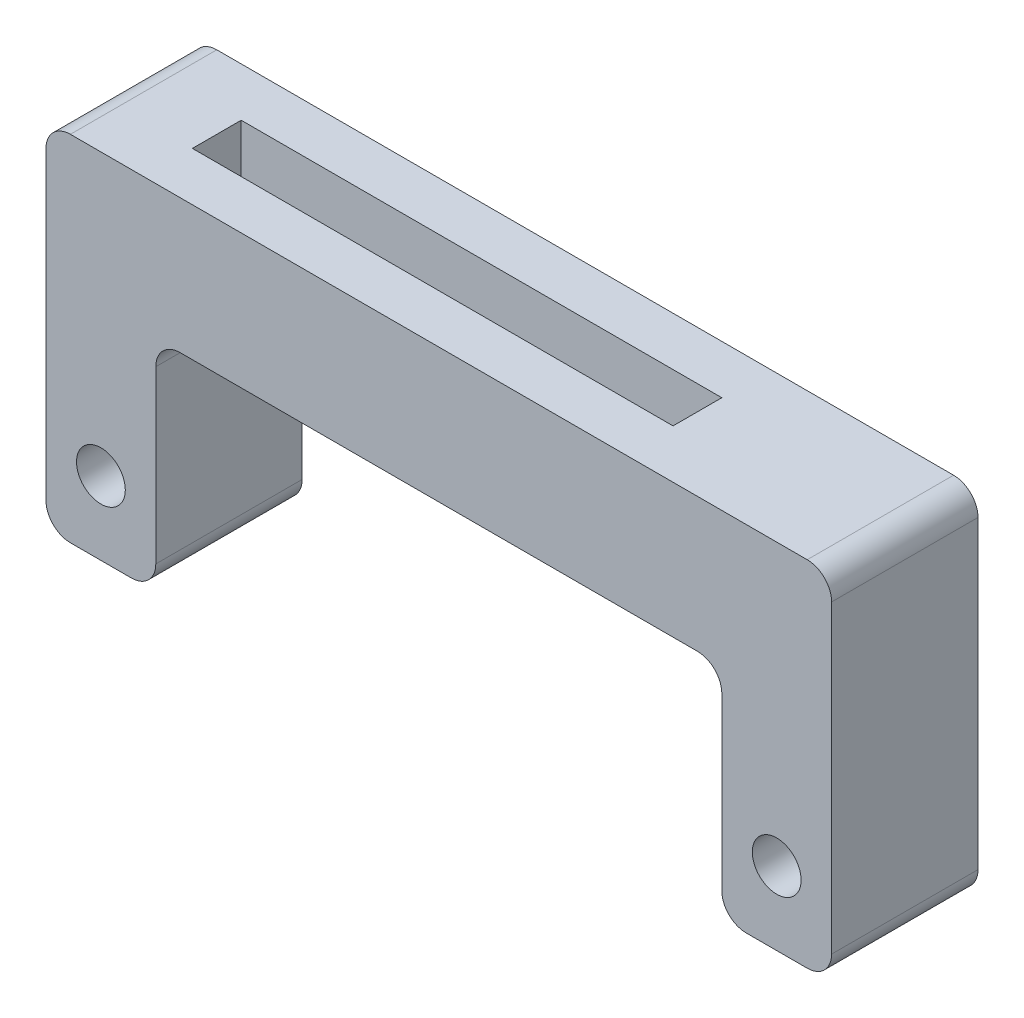
SolidWorks part; units mm, degrees
ref_plane "Front Plane" through (0, 0, 0) normal (0, 0, 1) x (1, 0, 0)
ref_plane "Top Plane" through (0, 0, 0) normal (0, 1, 0) x (1, 0, 0)
ref_plane "Right Plane" through (0, 0, 0) normal (1, 0, 0) x (0, 0, -1)
sketch "Sketch2" plane through (0, 0, 0) normal (0, 0, 1) x (1, 0, 0)
  line L1 (-16.1, -7.25) -> (16.1, -7.25)
  line L2 (-16.1, -7.25) -> (-16.1, 7.25)
  line L3 (-16.1, 7.25) -> (16.1, 7.25)
  line L4 (16.1, -7.25) -> (16.1, 7.25)
  line L5 (-16.1, -7.25) -> (16.1, 7.25) construction
  line L6 (-16.1, 7.25) -> (16.1, -7.25) construction
  point P0 (0, 0)
  dimension "D1" = 14.5
  dimension "D2" = 32.2
extrude "Boss-Extrude1" add sketch "Sketch2" along normal mid plane 6
sketch "Sketch3" plane through (0, 7.25, 0) normal (0, 1, 0) x (1, 0, 0)
  line L0 (-16.1, -3) -> (-16.1, 3) construction
  line L1 (-12.1, 1) -> (7.6, 1)
  line L2 (-12.1, 1) -> (-12.1, -1)
  line L3 (-12.1, -1) -> (7.6, -1)
  line L4 (7.6, 1) -> (7.6, -1)
  line L5 (16.1, -3) -> (16.1, 3) construction
  line L6 (16.1, 3) -> (-16.1, 3) construction
  dimension "D1" = 2
  dimension "D2" = 4
  dimension "D3" = 8.5
  dimension "D4" = 2
extrude "Cut-Extrude1" cut sketch "Sketch3" against normal blind 2.5
sketch "Sketch4" plane through (0, 0, 3) normal (0, 0, 1) x (1, 0, 0)
  line L0 (-16.1, -7.25) -> (16.1, -7.25) construction
  line L1 (-11.6, -7.25) -> (11.6, -7.25)
  line L2 (-11.6, -7.25) -> (-11.6, 1.75)
  line L3 (-11.6, 1.75) -> (11.6, 1.75)
  line L4 (11.6, -7.25) -> (11.6, 1.75)
  line L5 (-16.1, 7.25) -> (-16.1, -7.25) construction
  line L6 (16.1, -7.25) -> (16.1, 7.25) construction
  dimension "D1" = 9
  dimension "D2" = 4.5
  dimension "D3" = 4.5
extrude "Cut-Extrude2" cut sketch "Sketch4" against normal through all
sketch "Sketch5" plane through (0, 0, 3) normal (0, 0, 1) x (1, 0, 0)
  line L0 (-16.1, 7.25) -> (-16.1, -7.25) construction
  line L1 (16.1, -7.25) -> (16.1, 7.25) construction
  line L2 (-16.1, -7.25) -> (-11.6, -7.25) construction
  circle A0 centre (-13.85, -4.25) radius 1
  circle A2 centre (13.85, -4.25) radius 1
  dimension "D1" = 2
  dimension "D2" = 2.25
  dimension "D3" = 2.25
  dimension "D4" = 3
extrude "Cut-Extrude3" cut sketch "Sketch5" against normal through all
fillet "Fillet1" radius 1 8 edges at (16.1, 7.25, 0) (16.1, -7.25, 0) (11.6, -7.25, 0) (11.6, 1.75, 0) (-11.6, 1.75, 0) (-11.6, -7.25, 0) (-16.1, -7.25, 0) (-16.1, 7.25, 0)
